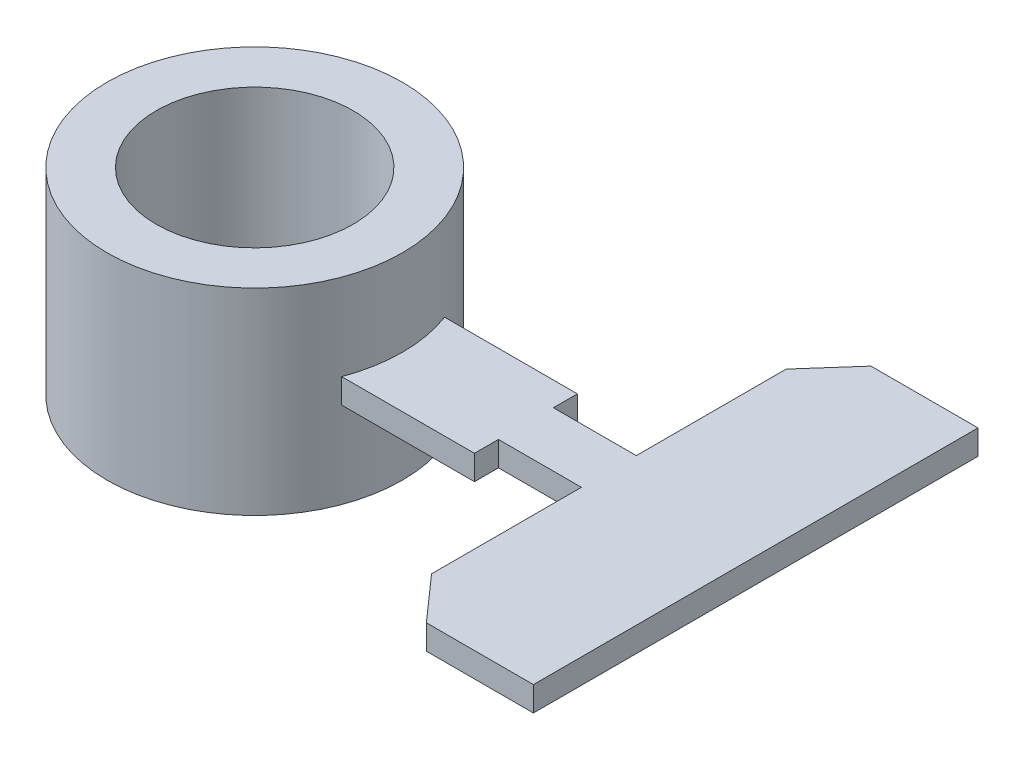
SolidWorks part; units mm, degrees
ref_plane "Front Plane" through (0, 0, 0) normal (0, 0, 1) x (1, 0, 0)
ref_plane "Top Plane" through (0, 0, 0) normal (0, 1, 0) x (1, 0, 0)
ref_plane "Right Plane" through (0, 0, 0) normal (1, 0, 0) x (0, 0, -1)
sketch "Sketch1" plane through (0, 0, 0) normal (0, 1, 0) x (1, 0, 0)
  circle A0 centre (0, 0) radius 30
  circle A1 centre (0, 0) radius 20
  dimension "D1" = 40
  dimension "D2" = 60
extrude "Boss-Extrude1" add sketch "Sketch1" along normal mid plane 40
sketch "Sketch2" plane through (0, 0, 0) normal (0, 1, 0) x (1, 0, 0)
  line L0 (0, 0) -> (117.7698, 0) construction
  line L1 (28.1204, 10.452) -> (55.0803, 10.452)
  line L2 (55.0803, 10.452) -> (55.0803, 5.5744)
  line L3 (55.0803, 5.5744) -> (71.9192, 5.5744)
  line L4 (71.9192, 5.5744) -> (71.9192, 36.0062)
  line L5 (71.9192, 36.0062) -> (80.0022, 45.1408)
  line L6 (80.0022, 45.1408) -> (101.7424, 45.1408)
  line L7 (101.7424, 45.1408) -> (101.7424, -45.1408)
  line L8 (55.0803, -10.452) -> (55.0803, -5.5744)
  line L9 (80.0022, -45.1408) -> (101.7424, -45.1408)
  line L10 (71.9192, -36.0062) -> (80.0022, -45.1408)
  line L11 (71.9192, -5.5744) -> (71.9192, -36.0062)
  line L12 (55.0803, -5.5744) -> (71.9192, -5.5744)
  line L13 (28.1204, -10.452) -> (55.0803, -10.452)
  circle A0 centre (0, 0) radius 30 construction
  arc A1 (28.1204, -10.452) -> (28.1204, 10.452) centre (0, 0) ccw
  point P16 (101.7424, 0)
extrude "Boss-Extrude2" add sketch "Sketch2" along normal mid plane 5
